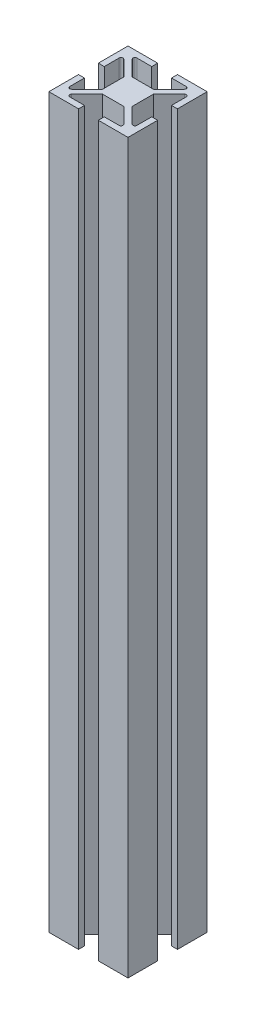
SolidWorks part; units mm, degrees
ref_plane "Plan de face" through (0, 0, 0) normal (0, 0, 1) x (1, 0, 0)
ref_plane "Plan de dessus" through (0, 0, 0) normal (0, 1, 0) x (1, 0, 0)
ref_plane "Plan de droite" through (0, 0, 0) normal (1, 0, 0) x (0, 0, -1)
sketch "Esquisse1" plane through (0, 0, 0) normal (0, 1, 0) x (1, 0, 0)
  line L0 (6.1245, 16.1036) -> (30.6226, 16.1036) construction
  line L6 (-11.5924, 0) -> (12.1076, 0) construction
  line L7 (0, 12.3466) -> (0, -12.7449) construction
  line L12 (-10, -10) -> (10, 10) construction
  line L59 (-10, -2.5) -> (-10, -10)
  line L60 (-10, -2.5) -> (-8.5, -2.5)
  line L69 (-8.5, -2.5) -> (-8.5, -6.2322)
  line L70 (-7.6464, -6.5858) -> (-3.75, -2.6893)
  line L73 (-6.5858, -7.6464) -> (-2.6893, -3.75)
  line L74 (-2.5, -8.5) -> (-6.2322, -8.5)
  line L75 (-2.5, -10) -> (-2.5, -8.5)
  line L76 (-2.5, -10) -> (-10, -10)
  line L77 (-2.5, 10) -> (-2.5, 8.5)
  line L78 (-2.5, 10) -> (-10, 10)
  line L79 (-10, 2.5) -> (-10, 10)
  line L80 (-10, 2.5) -> (-8.5, 2.5)
  line L81 (-8.5, 2.5) -> (-8.5, 6.2322)
  line L82 (-7.6464, 6.5858) -> (-3.75, 2.6893)
  line L83 (-6.5858, 7.6464) -> (-2.6893, 3.75)
  line L84 (-2.5, 8.5) -> (-6.2322, 8.5)
  line L85 (10, 2.5) -> (8.5, 2.5)
  line L86 (10, 2.5) -> (10, 10)
  line L87 (2.5, 10) -> (10, 10)
  line L88 (2.5, 10) -> (2.5, 8.5)
  line L89 (2.5, 8.5) -> (6.2322, 8.5)
  line L90 (6.5858, 7.6464) -> (2.6893, 3.75)
  line L91 (7.6464, 6.5858) -> (3.75, 2.6893)
  line L92 (8.5, 2.5) -> (8.5, 6.2322)
  line L93 (2.5, -10) -> (2.5, -8.5)
  line L94 (2.5, -10) -> (10, -10)
  line L95 (10, -2.5) -> (10, -10)
  line L96 (10, -2.5) -> (8.5, -2.5)
  line L97 (8.5, -2.5) -> (8.5, -6.2322)
  line L98 (7.6464, -6.5858) -> (3.75, -2.6893)
  line L99 (6.5858, -7.6464) -> (2.6893, -3.75)
  line L100 (2.5, -8.5) -> (6.2322, -8.5)
  line L101 (-3.75, 2.6893) -> (-3.75, -2.6893)
  line L102 (-2.6893, -3.75) -> (2.6893, -3.75)
  line L103 (-2.6893, 3.75) -> (2.6893, 3.75)
  line L104 (3.75, 2.6893) -> (3.75, -2.6893)
  arc A0 (-8.5, 6.2322) -> (-7.6464, 6.5858) centre (-8, 6.2322) cw
  arc A1 (-8.5, -6.2322) -> (-7.6464, -6.5858) centre (-8, -6.2322) ccw
  arc A2 (-6.5858, -7.6464) -> (-6.2322, -8.5) centre (-6.2322, -8) ccw
  arc A3 (6.5858, -7.6464) -> (6.2322, -8.5) centre (6.2322, -8) cw
  arc A4 (8.5, -6.2322) -> (7.6464, -6.5858) centre (8, -6.2322) cw
  arc A5 (7.6464, 6.5858) -> (8.5, 6.2322) centre (8, 6.2322) cw
  arc A6 (6.2322, 8.5) -> (6.5858, 7.6464) centre (6.2322, 8) cw
  arc A7 (-6.5858, 7.6464) -> (-6.2322, 8.5) centre (-6.2322, 8) cw
  point P7 (-2.5, -9.25)
  point P8 (2.5, -9.25)
  point P15 (-8.5, -7.4393)
  point P51 (0, 0)
  point P52 (-7.4393, -8.5)
  dimension "D2" = 5
  dimension "D7" = 0.5
  dimension "D1" = 20
  dimension "D3" = 4
  dimension "D4" = 7.5
  dimension "D5" = 1.5
  dimension "D6" = 1.5
extrude "Boss.-Extru.1" add sketch "Esquisse1" along normal blind 184
